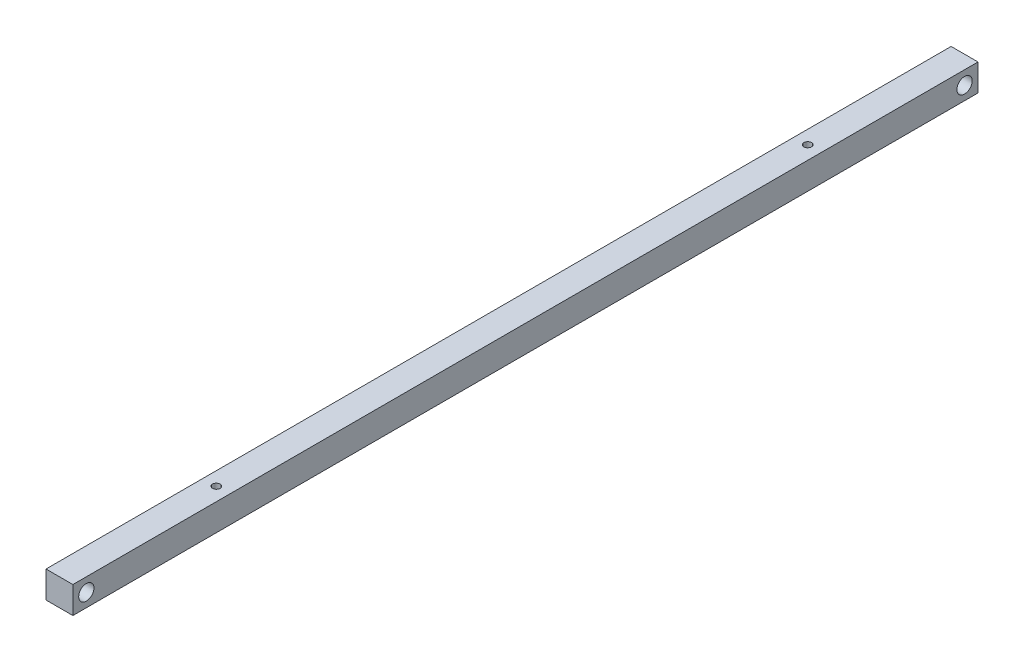
SolidWorks part; units mm, degrees
ref_plane "Ön Düzlem" through (0, 0, 0) normal (0, 0, 1) x (1, 0, 0)
ref_plane "Üst Düzlem" through (0, 0, 0) normal (0, 1, 0) x (1, 0, 0)
ref_plane "Sağ Düzlem" through (0, 0, 0) normal (1, 0, 0) x (0, 0, -1)
sketch "Çizim1" plane through (0, 0, 0) normal (0, 0, 1) x (1, 0, 0)
  line L1 (-7.5, -7.5) -> (7.5, -7.5)
  line L2 (-7.5, -7.5) -> (-7.5, 7.5)
  line L3 (-7.5, 7.5) -> (7.5, 7.5)
  line L4 (7.5, -7.5) -> (7.5, 7.5)
  line L5 (-7.5, -7.5) -> (7.5, 7.5) construction
  line L6 (-7.5, 7.5) -> (7.5, -7.5) construction
  point P0 (0, 0)
  dimension "D1" = 15
extrude "Yükseklik-Ekstrüzyon1" add sketch "Çizim1" along normal mid plane 505
hole_wizard "Delik2" positions "3B Çizim2" profile "Çizim3" legacy
sketch3d "3B Çizim2"
  line L0 (-7.5, 7.5, 252.5) -> (-7.5, -7.5, 252.5) construction
  point P0 (-7.5, 0, 245)
  point P6 (-7.5, 0, 252.5)
  dimension "D1" = 7.5
sketch "Çizim3" plane through (-7.5, 0, 245) normal (0, 1, 0) x (0, 0, 1)
  line L0 (0, 0) -> (0, 15)
  line L1 (0, 15) -> (4.25, 15)
  line L2 (4.25, 15) -> (4.25, 8)
  line L3 (4.25, 8) -> (7, 8)
  line L4 (7, 8) -> (7, 0)
  line L5 (7, 0) -> (0, 0)
  line L6 (0, 110) -> (0, -10) construction
  dimension "Diameter" = 8.5
  dimension "Depth" = 15
  dimension "C-Bore Diameter" = 14
  dimension "C-Bore Depth" = 8
mirror "Aynalama1" about plane through (0, 0, 0) normal (0, 0, 1) of "Delik2"
hole_wizard "M5 Dişli Delik1" positions "Çizim4" profile "Çizim5" tap size "M5" standard "ISO" end condition through all
sketch "Çizim4" plane through (0, -7.5, 0) normal (0, -1, 0) x (-1, 0, 0)
  point P0 (0, -165)
  dimension "D1" = 165
sketch "Çizim5" plane through (0, -7.5, 165) normal (1, 0, 0) x (0, 0, -1)
  line L0 (0, 0) -> (0, 15)
  line L1 (0, 15) -> (2.1, 15)
  line L2 (2.1, 15) -> (2.1, 0.425)
  line L3 (2.1, 0.425) -> (2.525, 0)
  line L5 (2.525, 0) -> (0, 0)
  line L6 (-2.1, 0.425) -> (-2.525, 0) construction
  line L11 (0, -6.35) -> (0, 107.95) construction
  dimension "Thru Tap Drill Dia." = 4.2
  dimension "Thru Tap Drill Depth" = 15
  dimension "Near C'Sink Dia." = 5.05
  dimension "Near C'Sink Angle" = 90
cosmetic thread "Delik Dişi1" parameters "D2"=5
mirror "Aynalama2" about plane through (0, 0, 0) normal (0, 0, 1) of "M5 Dişli Delik1"
cosmetic thread "Delik Dişi2" parameters "D2"=5
